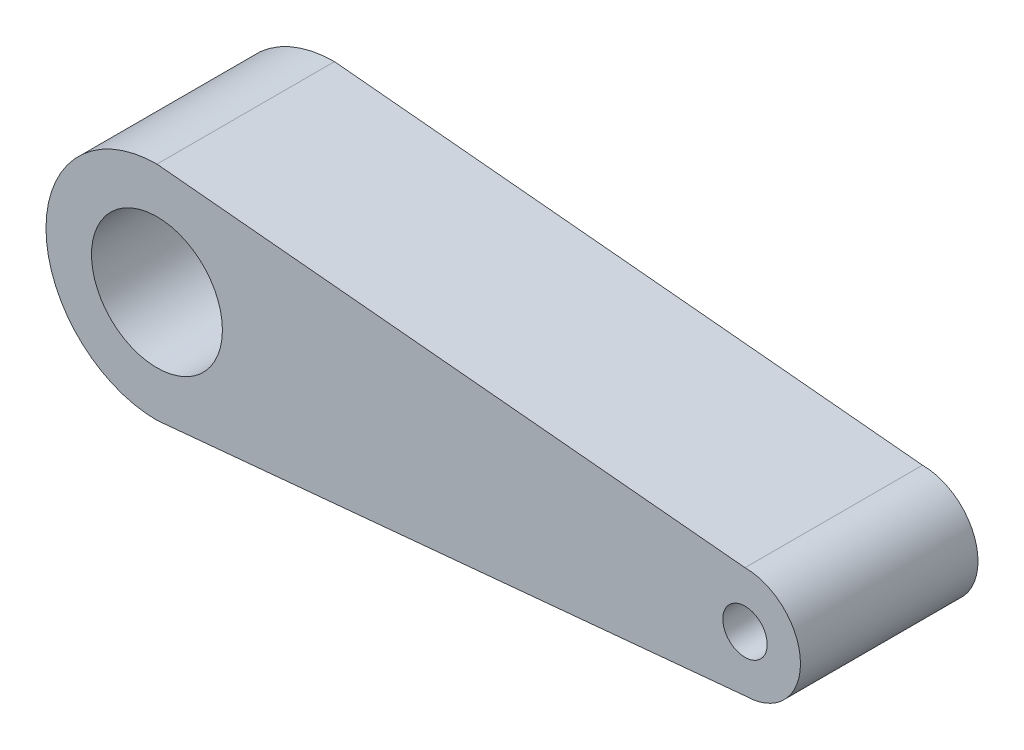
SolidWorks part; units mm, degrees
ref_plane "Plan de face" through (0, 0, 0) normal (0, 0, 1) x (1, 0, 0)
ref_plane "Plan de dessus" through (0, 0, 0) normal (0, 1, 0) x (1, 0, 0)
ref_plane "Plan de droite" through (0, 0, 0) normal (1, 0, 0) x (0, 0, -1)
sketch "Esquisse1" plane through (0, 0, 0) normal (0, 0, 1) x (1, 0, 0)
  line L0 (0, 5) -> (26.5, 2.5)
  line L1 (26.5, 2.5) -> (26.5, -2.5)
  line L2 (26.5, -2.5) -> (0, -5)
  line L3 (0, 5) -> (0, -5) construction
  line L4 (-5, 0) -> (29, 0) construction
  circle A0 centre (0, 0) radius 2.95
  arc A1 (0, 5) -> (0, -5) centre (0, 0) ccw
  arc A2 (26.5, 2.5) -> (26.5, -2.5) centre (26.5, 0) cw
  circle A3 centre (26.5, 0) radius 1
  point P9 (26.5, 0)
  dimension "D1" = 34
  dimension "D2" = 5.9
  dimension "D3" = 5
  dimension "D4" = 2.5
  dimension "D5" = 2
extrude "Boss.-Extru.1" add sketch "Esquisse1" along normal blind 8 contours A3 L1 L0 A1 L2 A0 | A3 L1 A2
